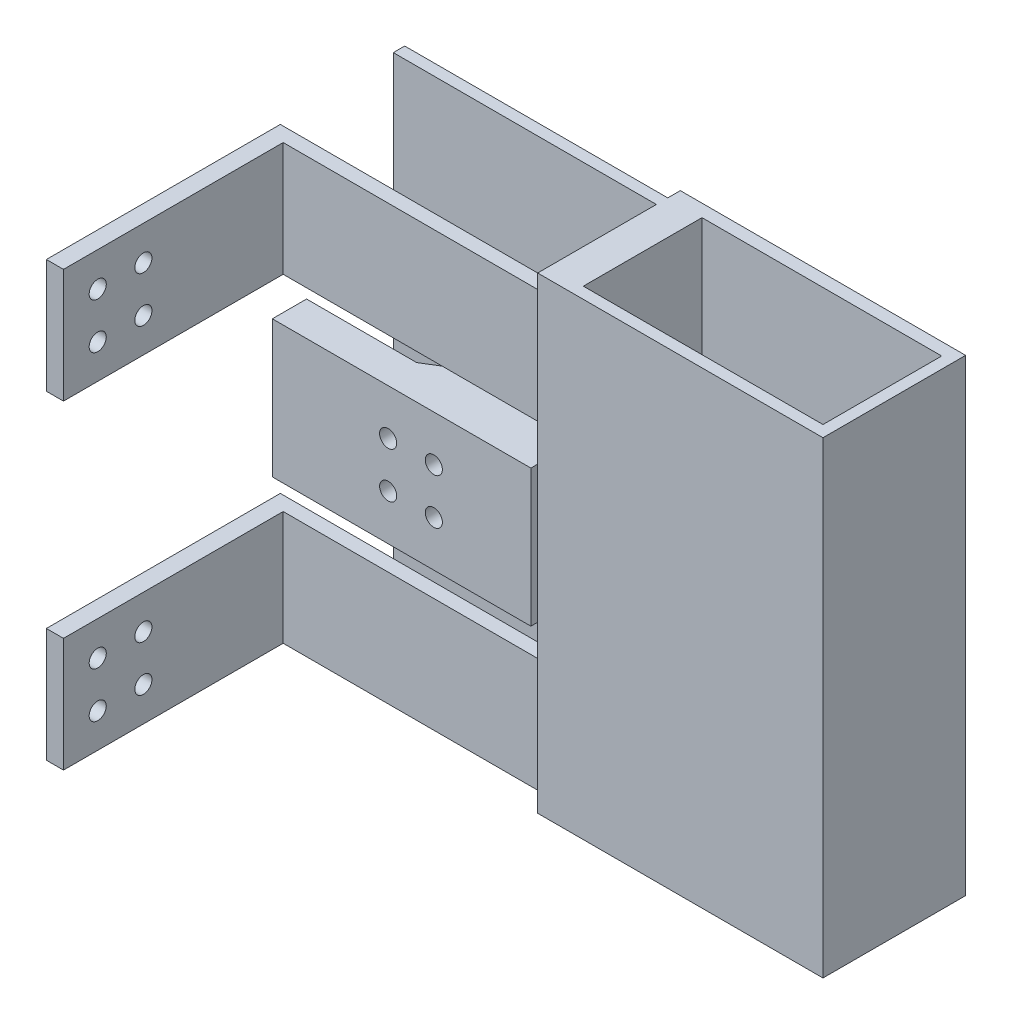
SolidWorks part; units mm, degrees
material "ABS"
ref_plane "Front Plane" through (0, 0, 0) normal (0, 0, 1) x (1, 0, 0)
ref_plane "Top Plane" through (0, 0, 0) normal (0, 1, 0) x (1, 0, 0)
ref_plane "Right Plane" through (0, 0, 0) normal (1, 0, 0) x (0, 0, -1)
ref_plane "P_rear_deck" through (-72.6, 0, 0) normal (1, 0, 0) x (0, 0, -1)
sketch "Sketch1" plane through (-72.6, 0, 0) normal (1, 0, 0) x (0, 0, -1)
  line L1 (53, -41) -> (28, -41)
  line L2 (53, -41) -> (53, 41)
  line L3 (53, 41) -> (28, 41)
  line L4 (28, -41) -> (28, 41)
extrude "Boss-Extrude1" add sketch "Sketch1" along normal blind 6
ref_plane "P_spine_upri" through (0, 0, -32.8) normal (0, 0, 1) x (1, 0, 0)
sketch "Sketch2" plane through (0, 0, -32.8) normal (0, 0, 1) x (1, 0, 0)
  line L1 (-117.9, -12) -> (-72.59, -12)
  line L2 (-117.9, -12) -> (-117.9, 12)
  line L3 (-117.9, 12) -> (-72.59, 12)
  line L4 (-72.59, -12) -> (-72.59, 12)
extrude "Boss-Extrude2" add sketch "Sketch2" along normal blind 6
ref_plane "P_gusset_y+9" through (0, 9, 0) normal (0, 1, 0) x (1, 0, 0)
sketch "Sketch3" plane through (0, 9, 0) normal (0, 1, 0) x (1, 0, 0)
  line L0 (-72.6, 32.8) -> (-72.6, 48.8)
  line L1 (-45.1, 32.8) -> (45.1, 32.8) construction
  line L2 (-72.6, -37.565) -> (-72.6, 37.565) construction
  line L3 (-72.6, 48.8) -> (-98.6, 32.8)
  line L4 (-98.6, 32.8) -> (-72.6, 32.8)
extrude "Boss-Extrude3" add sketch "Sketch3" along normal blind 3
ref_plane "P_gusset_y-1" through (0, -12, 0) normal (0, 1, 0) x (1, 0, 0)
sketch "Sketch4" plane through (0, -12, 0) normal (0, 1, 0) x (1, 0, 0)
  line L0 (-72.6, 32.8) -> (-72.6, 48.8)
  line L1 (-45.1, 32.8) -> (45.1, 32.8) construction
  line L2 (-72.6, -37.565) -> (-72.6, 37.565) construction
  line L3 (-72.6, 48.8) -> (-98.6, 32.8)
  line L4 (-98.6, 32.8) -> (-72.6, 32.8)
extrude "Boss-Extrude4" add sketch "Sketch4" along normal blind 3
ref_plane "P_H1_cradle_" through (-120.7, 0, 0) normal (1, 0, 0) x (0, 0, -1)
sketch "Sketch5" plane through (-120.7, 0, 0) normal (1, 0, 0) x (0, 0, -1)
  line L1 (-10, 18) -> (31, 18)
  line L2 (-10, 18) -> (-10, 38)
  line L3 (-10, 38) -> (31, 38)
  line L4 (31, 18) -> (31, 38)
extrude "Boss-Extrude5" add sketch "Sketch5" along normal blind 3
ref_plane "Plane6" through (0, 0, -31) normal (0, 0, 1) x (1, 0, 0)
sketch "Sketch6" plane through (0, 0, -31) normal (0, 0, 1) x (1, 0, 0)
  line L0 (-120.7, -37.565) -> (-120.7, 37.565) construction
  line L1 (-120.7, 18) -> (-72.6, 18)
  line L2 (-120.7, 18) -> (-120.7, 38)
  line L3 (-120.7, 38) -> (-72.6, 38)
  line L4 (-72.6, 18) -> (-72.6, 38)
  line L5 (-72.6, -37.565) -> (-72.6, 37.565) construction
extrude "Boss-Extrude6" add sketch "Sketch6" along normal blind 2.5
ref_plane "Plane7" through (-120.7, 0, 0) normal (1, 0, 0) x (0, 0, -1)
sketch "Sketch7" plane through (-120.7, 0, 0) normal (1, 0, 0) x (0, 0, -1)
  line L0 (31, 45.1) -> (31, -45.1) construction
  line L1 (-10, -38) -> (31, -38)
  line L2 (-10, -38) -> (-10, -18)
  line L3 (-10, -18) -> (31, -18)
  line L4 (31, -38) -> (31, -18)
extrude "Boss-Extrude7" add sketch "Sketch7" along normal blind 3
ref_plane "Plane8" through (0, 0, -31) normal (0, 0, 1) x (1, 0, 0)
sketch "Sketch8" plane through (0, 0, -31) normal (0, 0, 1) x (1, 0, 0)
  line L0 (-120.7, -37.565) -> (-120.7, 37.565) construction
  line L1 (-120.7, -38) -> (-72.6, -38)
  line L2 (-120.7, -38) -> (-120.7, -18)
  line L3 (-120.7, -18) -> (-72.6, -18)
  line L4 (-72.6, -38) -> (-72.6, -18)
  line L5 (-72.6, -37.565) -> (-72.6, 37.565) construction
extrude "Boss-Extrude8" add sketch "Sketch8" along normal blind 2.5
ref_plane "P_h1" through (-117.7, 0, 0) normal (1, 0, 0) x (0, 0, -1)
sketch "Sketch9" plane through (-117.7, 0, 0) normal (1, 0, 0) x (0, 0, -1)
  circle A0 centre (-4, 24) radius 1.5
  circle A1 centre (4, 24) radius 1.5
  circle A2 centre (-4, 32) radius 1.5
  circle A3 centre (4, 32) radius 1.5
  circle A4 centre (-4, -32) radius 1.5
  circle A5 centre (4, -32) radius 1.5
  circle A6 centre (-4, -24) radius 1.5
  circle A7 centre (4, -24) radius 1.5
extrude "Cut-Extrude1" cut sketch "Sketch9" against normal blind 3
ref_plane "P_spine" through (0, 0, -26.8) normal (0, 0, 1) x (1, 0, 0)
sketch "Sketch10" plane through (0, 0, -26.8) normal (0, 0, 1) x (1, 0, 0)
  circle A0 centre (-89.6, 4) radius 1.5
  circle A1 centre (-89.6, -4) radius 1.5
  circle A2 centre (-97.6, 4) radius 1.5
  circle A3 centre (-97.6, -4) radius 1.5
extrude "Cut-Extrude2" cut sketch "Sketch10" against normal blind 3
ref_plane "P_controller" through (0, 0, -50.8) normal (0, 0, 1) x (1, 0, 0)
sketch "Sketch11" plane through (0, 0, -50.8) normal (0, 0, 1) x (1, 0, 0)
  line L0 (-72.6, -37.565) -> (-72.6, 37.565) construction
  line L1 (-118.7, -41) -> (-72.6, -41)
  line L2 (-118.7, -41) -> (-118.7, 41)
  line L3 (-118.7, 41) -> (-72.6, 41)
  line L4 (-72.6, -41) -> (-72.6, 41)
extrude "Boss-Extrude9" add sketch "Sketch11" along normal blind 2
ref_plane "Z-55_80" through (0, 0, -55.8) normal (0, 0, 1) x (1, 0, 0)
sketch "Sketch12" plane through (0, 0, -55.8) normal (0, 0, 1) x (1, 0, 0)
  circle A0 centre (-115.15, -29) radius 3
  circle A1 centre (-115.15, 29) radius 3
  circle A2 centre (-76.15, -29) radius 3
  circle A3 centre (-76.15, 29) radius 3
extrude "Boss-Extrude10" add sketch "Sketch12" along normal blind 5
ref_plane "Z-58_30" through (0, 0, -58.3) normal (0, 0, 1) x (1, 0, 0)
sketch "Sketch13" plane through (0, 0, -58.3) normal (0, 0, 1) x (1, 0, 0)
  circle A0 centre (-115.15, -29) radius 1.4
  circle A1 centre (-115.15, 29) radius 1.4
  circle A2 centre (-76.15, -29) radius 1.4
  circle A3 centre (-76.15, 29) radius 1.4
extrude "Boss-Extrude11" add sketch "Sketch13" along normal blind 2.5
ref_plane "P_battery_tr" through (-66.6, 0, 0) normal (1, 0, 0) x (0, 0, -1)
sketch "Sketch14" plane through (-66.6, 0, 0) normal (1, 0, 0) x (0, 0, -1)
  line L0 (28, -41) -> (53, -41) construction
  line L1 (30, -41) -> (28, -41)
  line L2 (30, -41) -> (30, 41)
  line L3 (30, 41) -> (28, 41)
  line L4 (28, -41) -> (28, 41)
extrude "Boss-Extrude12" add sketch "Sketch14" along normal blind 42
ref_plane "Plane15" through (-66.6, 0, 0) normal (1, 0, 0) x (0, 0, -1)
sketch "Sketch15" plane through (-66.6, 0, 0) normal (1, 0, 0) x (0, 0, -1)
  line L0 (50.8, 45.1) -> (50.8, -45.1) construction
  line L1 (53, -41) -> (50.8, -41)
  line L2 (53, -41) -> (53, 41)
  line L3 (53, 41) -> (50.8, 41)
  line L4 (50.8, -41) -> (50.8, 41)
extrude "Boss-Extrude13" add sketch "Sketch15" along normal blind 42
ref_plane "Plane16" through (-66.6, 0, 0) normal (1, 0, 0) x (0, 0, -1)
sketch "Sketch16" plane through (-66.6, 0, 0) normal (1, 0, 0) x (0, 0, -1)
  line L0 (50.8, 45.1) -> (50.8, -45.1) construction
  line L1 (50.8, -41) -> (30, -41)
  line L2 (50.8, -41) -> (50.8, -39)
  line L3 (50.8, -39) -> (30, -39)
  line L4 (30, -41) -> (30, -39)
  line L5 (30, -41) -> (30, 41) construction
extrude "Boss-Extrude14" add sketch "Sketch16" along normal blind 42
ref_plane "Plane17" through (-24.6, 0, 0) normal (1, 0, 0) x (0, 0, -1)
sketch "Sketch17" plane through (-24.6, 0, 0) normal (1, 0, 0) x (0, 0, -1)
  line L1 (53, -41) -> (28, -41)
  line L2 (53, -41) -> (53, 41)
  line L3 (53, 41) -> (28, 41)
  line L4 (28, -41) -> (28, 41)
extrude "Boss-Extrude15" add sketch "Sketch17" along normal blind 2
